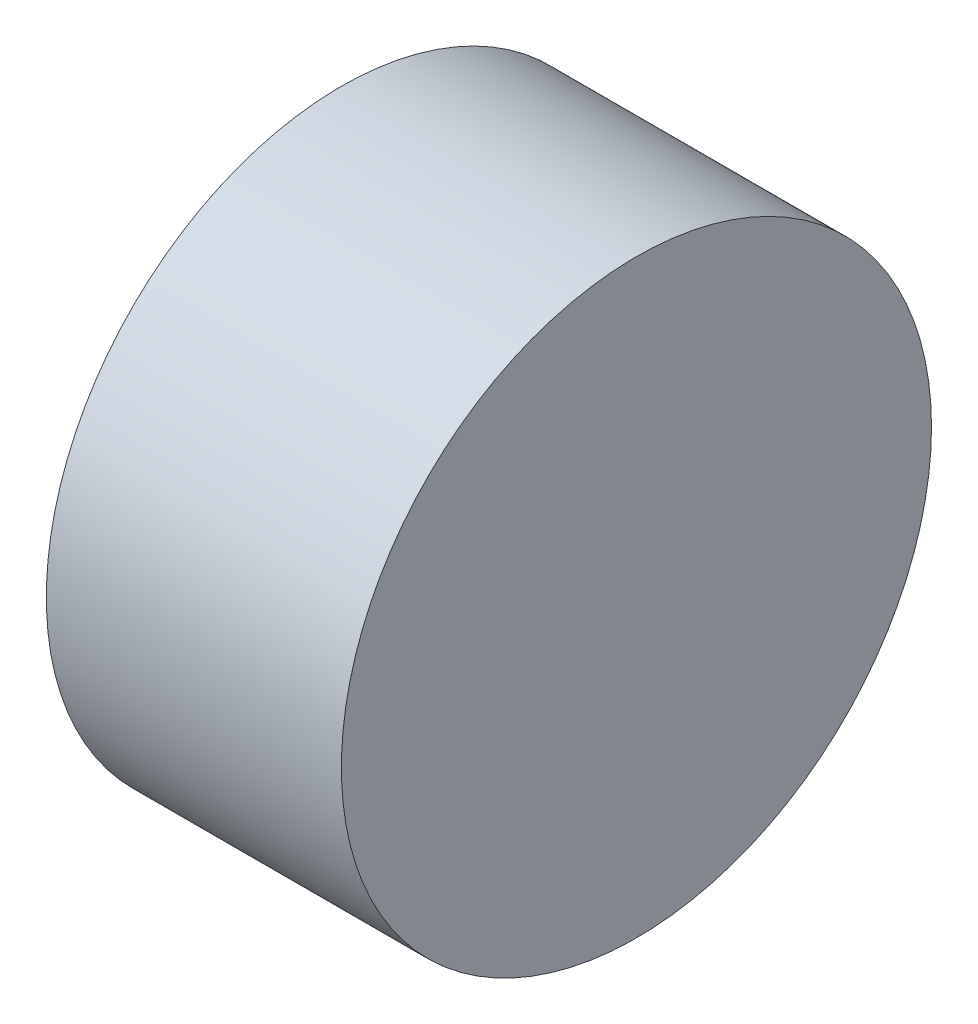
SolidWorks part; units mm, degrees
ref_plane "Front Plane" through (0, 0, 0) normal (0, 0, 1) x (1, 0, 0)
ref_plane "Top Plane" through (0, 0, 0) normal (0, 1, 0) x (1, 0, 0)
ref_plane "Right Plane" through (0, 0, 0) normal (1, 0, 0) x (0, 0, -1)
sketch "Sketch1" plane through (0, 0, 0) normal (1, 0, 0) x (0, 0, -1)
  circle A0 centre (0, 0) radius 1
  dimension "D1" = 2
extrude "Boss-Extrude1" add sketch "Sketch1" along normal blind 1
